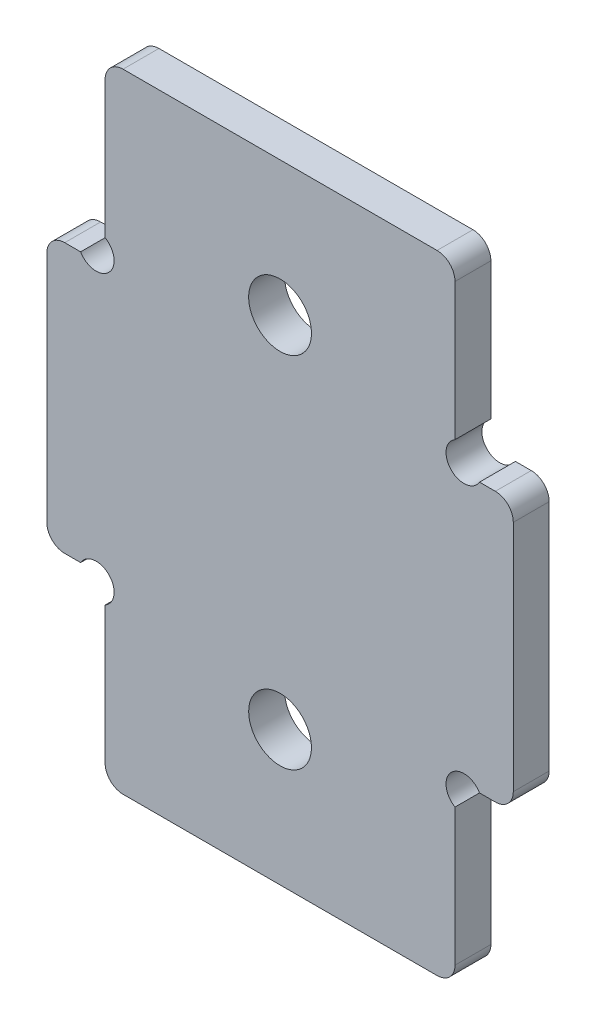
SolidWorks part; units mm, degrees
ref_plane "前视基准面" through (0, 0, 0) normal (0, 0, 1) x (1, 0, 0)
ref_plane "上视基准面" through (0, 0, 0) normal (0, 1, 0) x (1, 0, 0)
ref_plane "右视基准面" through (0, 0, 0) normal (1, 0, 0) x (0, 0, -1)
other "Configuration Table"
sketch "草图1" plane through (0, 0, 0) normal (0, 0, 1) x (1, 0, 0)
  line L0 (0, 35) -> (0, 0)
  line L1 (0, 0) -> (19.5, 0)
  line L2 (19.5, 0) -> (19.5, 35)
  line L3 (19.5, 35) -> (0, 35)
  dimension "D1" = 19.5
  dimension "D2" = 35
extrude "凸台-拉伸1" add sketch "草图1" along normal blind 2
sketch "草图3" plane through (0, 0, 2) normal (0, 0, 1) x (1, 0, 0)
  line L0 (9.75, 57.4673) -> (9.75, -9.4303) construction
  line L1 (0, 0) -> (19.5, 0) construction
  line L2 (-12.6648, 17.5) -> (30.1755, 17.5) construction
  line L3 (19.5, 0) -> (19.5, 35) construction
  circle A0 centre (9.75, 27.5) radius 1.75
  circle A1 centre (9.75, 7.5) radius 1.75
  point P4 (9.75, 0)
  point P9 (19.5, 17.5)
  dimension "D1" = 10
  dimension "D2" = 3.5
extrude "切除-拉伸1" cut sketch "草图3" against normal through all
sketch "草图4" plane through (0, 0, 2) normal (0, 0, 1) x (1, 0, 0)
  line L0 (-7.7439, 17.5) -> (25.908, 17.5) construction
  line L1 (19.5, 0) -> (19.5, 35) construction
  line L2 (19.5, 10) -> (19.5, 25)
  line L3 (19.5, 25) -> (22.75, 25)
  line L4 (22.75, 25) -> (22.75, 10)
  line L5 (19.5, 10) -> (22.75, 10)
  line L6 (9.75, 43.3785) -> (9.75, -7.0718) construction
  line L7 (0, 0) -> (19.5, 0) construction
  line L8 (0, 10) -> (-3.25, 10)
  line L9 (-3.25, 25) -> (-3.25, 10)
  line L10 (0, 25) -> (-3.25, 25)
  line L11 (0, 10) -> (0, 25)
  point P4 (19.5, 17.5)
  point P10 (19.5, 17.5)
  point P11 (22.75, 17.5)
  point P15 (9.75, 0)
  point P20 (-3.25, 17.5)
  point P21 (0, 17.5)
  dimension "D1" = 3.25
  dimension "D2" = 7.5
extrude "凸台-拉伸2" add sketch "草图4" against normal blind 2
sketch "草图5" plane through (0, 0, 2) normal (0, 0, 1) x (1, 0, 0)
  line L0 (19.5, 25) -> (21.2317, 26.7317) construction
  line L1 (22.75, 25) -> (19.5, 25) construction
  line L2 (-17.0849, 17.5) -> (38.1723, 17.5) construction
  line L3 (9.75, 43.3683) -> (9.75, -7.3222) construction
  line L4 (19.5, 35) -> (0, 35) construction
  line L5 (22.75, 10) -> (22.75, 25) construction
  line L6 (19.5, 10) -> (21.2317, 8.2683) construction
  line L7 (0, 10) -> (-1.7317, 8.2683) construction
  line L8 (0, 25) -> (-1.7317, 26.7317) construction
  circle A4 centre (20, 25.5) radius 1
  circle A5 centre (20, 9.5) radius 1
  circle A6 centre (-0.5, 9.5) radius 1
  circle A7 centre (-0.5, 25.5) radius 1
  point P17 (9.75, 35)
  point P20 (22.75, 17.5)
  dimension "D1" = 45
  dimension "D2" = 2
  dimension "D3" = 0.5
extrude "切除-拉伸2" cut sketch "草图5" against normal blind 10
fillet "圆角1" radius 1 8 edges at (0, 35, 1) (22.75, 25, 1) (22.75, 10, 1) (19.5, 0, 1) (0, 0, 1) (-3.25, 10, 1) (-3.25, 25, 1) (19.5, 35, 1)
